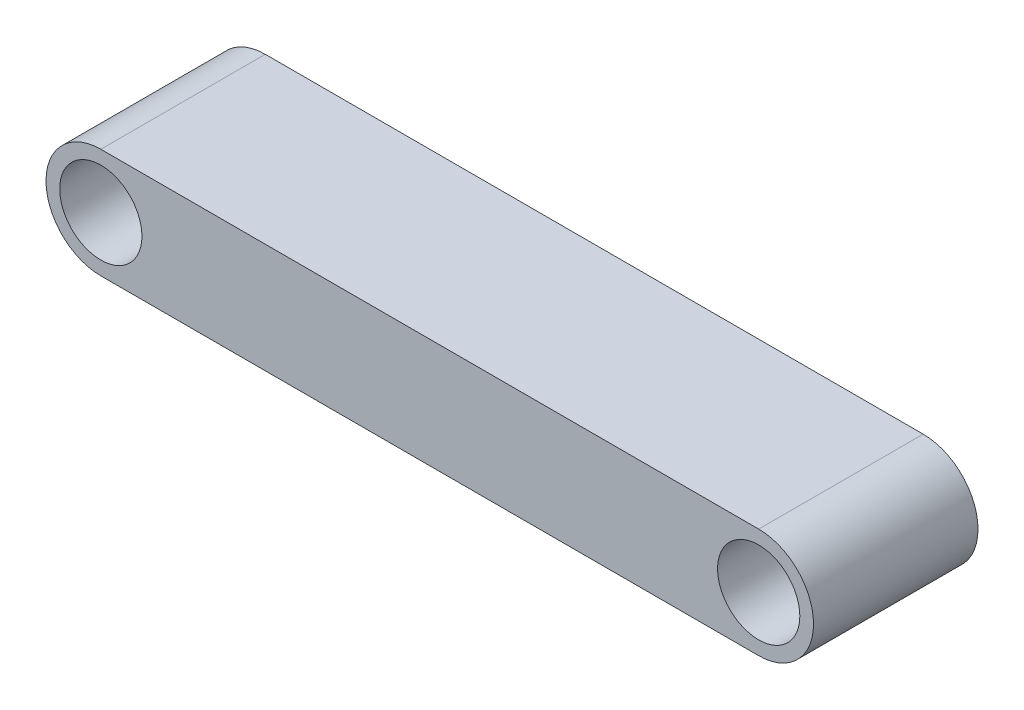
SolidWorks part; units mm, degrees
ref_plane "前视基准面" through (0, 0, 0) normal (0, 0, 1) x (1, 0, 0)
ref_plane "上视基准面" through (0, 0, 0) normal (0, 1, 0) x (1, 0, 0)
ref_plane "右视基准面" through (0, 0, 0) normal (1, 0, 0) x (0, 0, -1)
sketch "草图1" plane through (0, 0, 0) normal (0, 0, 1) x (1, 0, 0)
  line L1 (0, -2) -> (24, -2)
  line L2 (0, 2) -> (24, 2)
  arc A0 (0, -2) -> (0, 2) centre (0, 0) cw
  arc A1 (24, -2) -> (24, 2) centre (24, 0) ccw
  circle A2 centre (0, 0) radius 1.5
  circle A3 centre (24, 0) radius 1.5
  dimension "D2" = 3
  dimension "D3" = 3
  dimension "D1" = 24
  dimension "D4" = 4
extrude "凸台-拉伸1" add sketch "草图1" along normal blind 6
